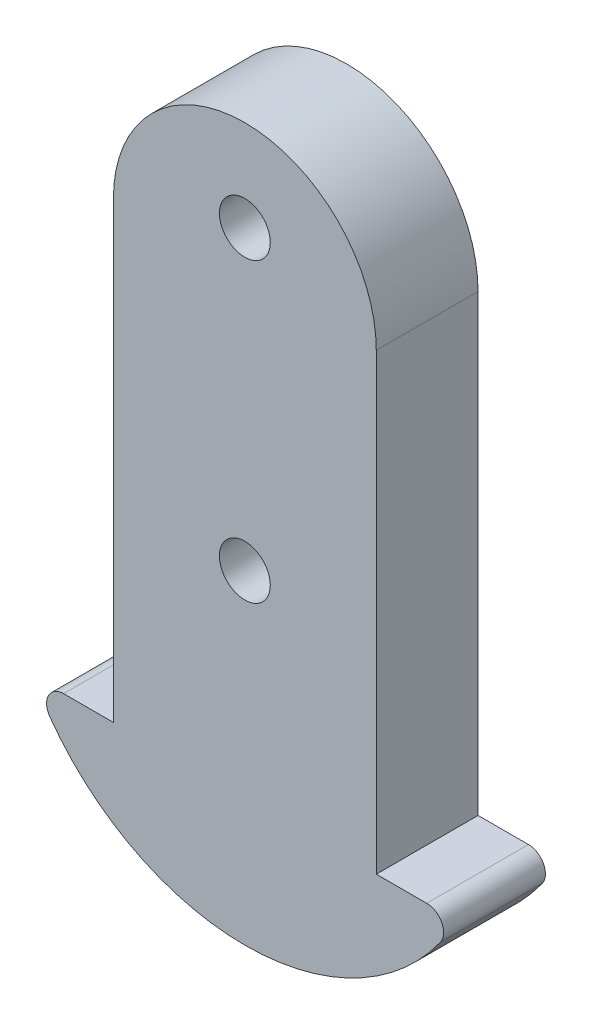
SolidWorks part; units mm, degrees
ref_plane "Front Plane" through (0, 0, 0) normal (0, 0, 1) x (1, 0, 0)
ref_plane "Top Plane" through (0, 0, 0) normal (0, 1, 0) x (1, 0, 0)
ref_plane "Right Plane" through (0, 0, 0) normal (1, 0, 0) x (0, 0, -1)
sketch "Sketch1" plane through (0, 0, 0) normal (0, 0, 1) x (1, 0, 0)
  line L0 (-0.0161, 16.5) -> (-0.0161, -16.5) construction
  line L6 (7.75, -16.375) -> (7.7339, -16.3409) construction
  line L9 (-10.7044, -18) -> (10.7044, -18)
  line L10 (7.7339, 8.75) -> (7.7339, -18)
  line L11 (-7.7661, 8.75) -> (-7.7661, -18)
  circle A0 centre (-0.0161, 11.125) radius 1.5
  circle A1 centre (-0.0161, -6.375) radius 1.5
  arc A2 (-11.5173, -19.5823) -> (11.5173, -19.5823) centre (0, -11.3333) ccw
  arc A3 (-10.7044, -18) -> (-11.5173, -19.5823) centre (-10.7044, -19) ccw
  arc A4 (10.7044, -18) -> (11.5173, -19.5823) centre (10.7044, -19) cw
  arc A6 (7.7339, 8.75) -> (-7.7661, 8.75) centre (-0.0161, 8.75) ccw
  arc A8 (7.7339, 8.75) -> (6.1525, 13.4415) centre (-0.0161, 8.75) ccw
  point P0 (0, 0)
  point P9 (-0.0161, 0)
  point P16 (3.875, -16.375)
  point P17 (0, -25.5)
  point P20 (-12.5, -16.375)
  point P23 (12.5, -16.375)
  dimension "D3" = 3
  dimension "D4" = 3
  dimension "D7" = 7.5
  dimension "D9" = 1
  dimension "D2" = 7.75
  dimension "D1" = 33
  dimension "D5" = 17.5
  dimension "D6" = 10
  dimension "D8" = 25
  dimension "D10" = 42
extrude "Boss-Extrude2" add sketch "Sketch1" along normal blind 6
ref_plane "Plane1" through (-7.7661, -18, 6) normal (0, -1, 0) x (-1, 0, 0)
sketch "Sketch4" plane through (0, 0, 6) normal (0, 0, 1) x (1, 0, 0)
sketch "Sketch6" plane through (0, 0, 6) normal (0, 0, 1) x (1, 0, 0)
